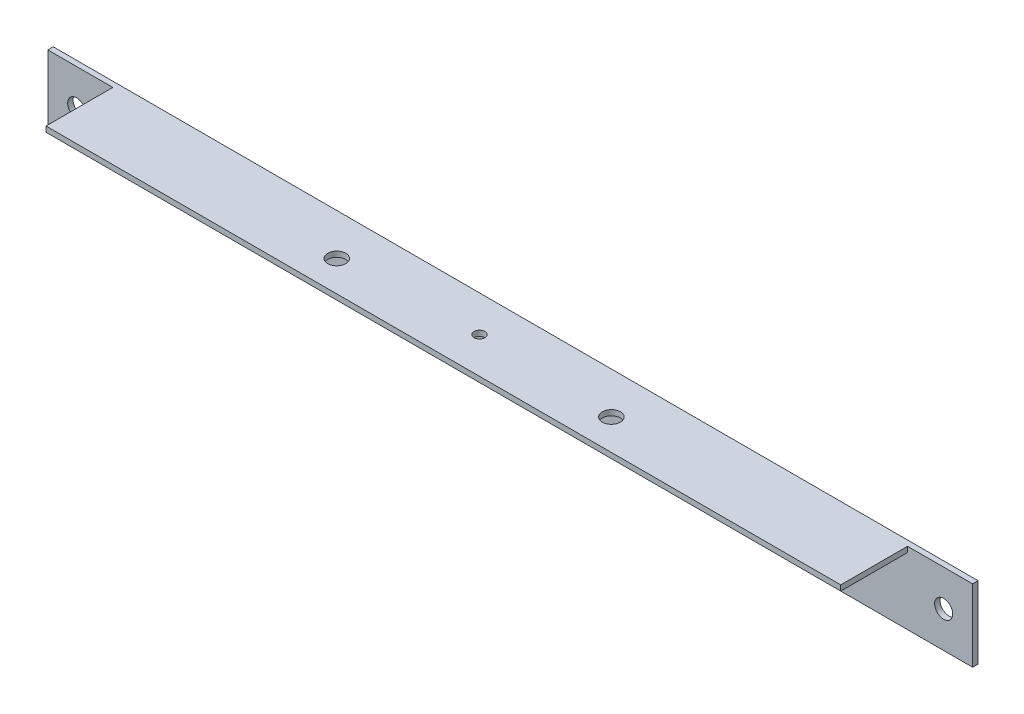
SolidWorks part; units mm, degrees
material "3.0205 (EN-AW 1200)"
ref_plane "Plan de face" through (0, 0, 0) normal (0, 0, 1) x (1, 0, 0)
ref_plane "Plan de dessus" through (0, 0, 0) normal (0, 1, 0) x (1, 0, 0)
ref_plane "Plan de droite" through (0, 0, 0) normal (1, 0, 0) x (0, 0, -1)
sketch "Esquisse1" plane through (0, 0, 0) normal (1, 0, 0) x (0, 0, -1)
  line L0 (-20, 0) -> (0, 0)
  line L1 (0, 0) -> (0, -20)
  dimension "D1" = 20
  dimension "D2" = 20
extrude "Extru.-Mince1" add sketch "Esquisse1" along normal mid plane 256 thin
sketch "Esquisse2" plane through (0, 0, 1.5) normal (0, 0, 1) x (1, 0, 0)
  line L0 (0, -20) -> (0, -1.5) construction
  line L1 (128, -20) -> (-128, -20) construction
  line L2 (128, -1.5) -> (-128, -1.5) construction
  circle A0 centre (-120, -10) radius 2.5
  circle A1 centre (120, -10) radius 2.5
  dimension "D1" = 240
  dimension "D2" = 10
  dimension "D3" = 5
extrude "Enlèv. mat.-Extru.1" cut sketch "Esquisse2" against normal blind 10
sketch "Esquisse3" plane through (0, -1.5, 0) normal (0, -1, 0) x (1, 0, 0)
  line L0 (128, 1.5) -> (-128, 1.5) construction
  line L1 (-128, 20) -> (-110, 20)
  line L2 (-128, 20) -> (-128, 1.5)
  line L3 (-128, 1.5) -> (-110, 1.5)
  line L4 (-110, 20) -> (-110, 1.5)
  line L5 (0, 0) -> (0, 20) construction
  line L6 (128, 20) -> (-128, 20) construction
  line L7 (110, 20) -> (110, 1.5)
  line L8 (128, 1.5) -> (110, 1.5)
  line L9 (128, 20) -> (128, 1.5)
  line L10 (128, 20) -> (110, 20)
  circle A0 centre (-38, 11.5) radius 2.5
  circle A1 centre (38, 11.5) radius 2.5
  dimension "D2" = 76
  dimension "D3" = 10
  dimension "D4" = 5
  dimension "D1" = 220
extrude "Enlèv. mat.-Extru.2" cut sketch "Esquisse3" against normal blind 10
sketch "Esquisse4" plane through (0, 0, 0) normal (0, 1, 0) x (1, 0, 0)
  line L0 (128, 0) -> (-128, 0) construction
  circle A0 centre (0, -10) radius 1.5
  dimension "D1" = 10
  dimension "D2" = 3
extrude "Enlèv. mat.-Extru.3" cut sketch "Esquisse4" against normal blind 5
sketch "Esquisse5" plane through (0, 0, 0) normal (0, 0, -1) x (-1, 0, 0)
  line L0 (0, 11) -> (0, -11) construction
  line L1 (-128, 0) -> (128, 0) construction
  circle A0 centre (-20, -10) radius 1.5
  circle A1 centre (20, -10) radius 1.5
  dimension "D1" = 40
  dimension "D3" = 3
  dimension "D2" = 10
extrude "Enlèv. mat.-Extru.4" cut sketch "Esquisse5" against normal blind 5
